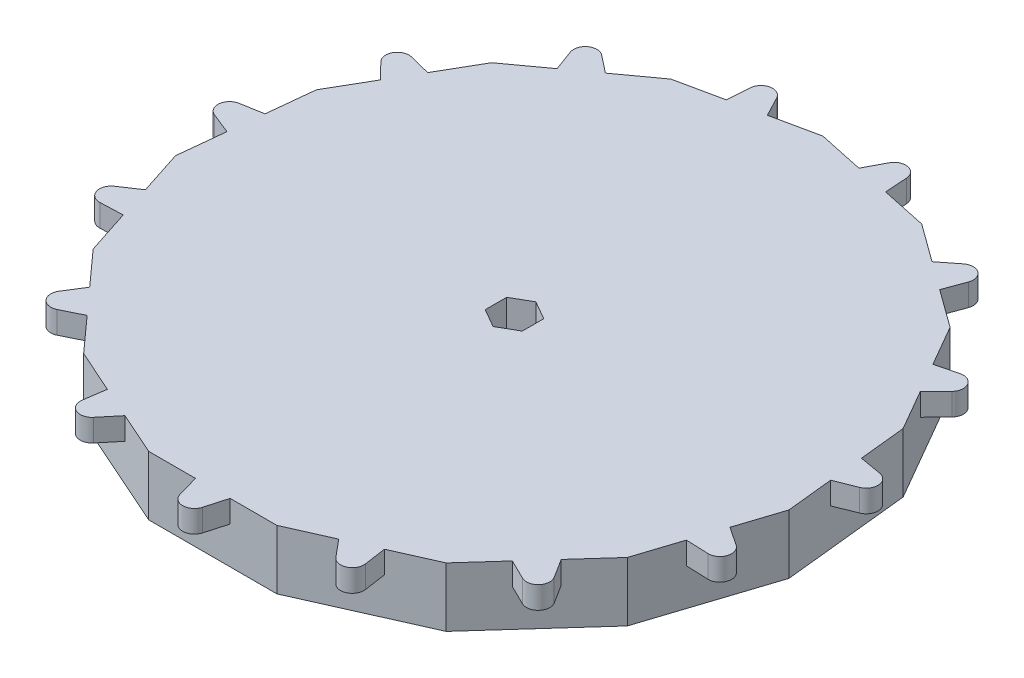
SolidWorks part; units mm, degrees
ref_plane "Front Plane" through (0, 0, 0) normal (0, 0, 1) x (1, 0, 0)
ref_plane "Top Plane" through (0, 0, 0) normal (0, 1, 0) x (1, 0, 0)
ref_plane "Right Plane" through (0, 0, 0) normal (1, 0, 0) x (0, 0, -1)
sketch "Sketch2" plane through (0, 0, 0) normal (0, 1, 0) x (1, 0, 0)
  line L18 (-48.0899, -66.1901) -> (-17.0104, -80.0275) construction
  line L37 (0, 81.8154) -> (-33.2773, 74.7421) construction
  line L38 (-33.2773, 74.7421) -> (-60.8007, 54.7452) construction
  line L39 (-60.8007, 54.7452) -> (-77.8111, 25.2824) construction
  line L40 (-77.8111, 25.2824) -> (-81.3672, -8.552) construction
  line L41 (-81.3672, -8.552) -> (-70.8542, -40.9077) construction
  line L42 (-70.8542, -40.9077) -> (-48.0899, -66.1901) construction
  line L43 (-17.0104, -80.0275) -> (17.0104, -80.0275) construction
  line L44 (17.0104, -80.0275) -> (48.0899, -66.1901) construction
  line L45 (48.0899, -66.1901) -> (70.8542, -40.9077) construction
  line L46 (70.8542, -40.9077) -> (81.3672, -8.552) construction
  line L47 (81.3672, -8.552) -> (77.8111, 25.2824) construction
  line L48 (77.8111, 25.2824) -> (60.8007, 54.7452) construction
  line L49 (60.8007, 54.7452) -> (33.2773, 74.7421) construction
  line L50 (33.2773, 74.7421) -> (0, 81.8154) construction
  line L51 (16.1106, 75.7943) -> (17.0907, 80.4055) construction
  line L52 (0, 79.2187) -> (-32.2211, 72.3699)
  line L53 (-32.2211, 72.3699) -> (-58.8709, 53.0076)
  line L54 (-58.8709, 53.0076) -> (-75.3414, 24.4799)
  line L55 (-75.3414, 24.4799) -> (-78.7847, -8.2806)
  line L56 (-78.7847, -8.2806) -> (-68.6054, -39.6093)
  line L57 (-68.6054, -39.6093) -> (-46.5636, -64.0892)
  line L58 (-46.5636, -64.0892) -> (-16.4705, -77.4875)
  line L59 (-16.4705, -77.4875) -> (16.4705, -77.4875)
  line L60 (16.4705, -77.4875) -> (46.5636, -64.0892)
  line L61 (46.5636, -64.0892) -> (68.6054, -39.6093)
  line L62 (68.6054, -39.6093) -> (78.7847, -8.2806)
  line L63 (78.7847, -8.2806) -> (75.3414, 24.4799)
  line L64 (75.3414, 24.4799) -> (58.8709, 53.0076)
  line L65 (58.8709, 53.0076) -> (32.2211, 72.3699)
  line L66 (32.2211, 72.3699) -> (0, 79.2187)
  line L67 (11.7627, 76.7184) -> (14.4414, 81.8016)
  line L68 (20.4584, 74.8701) -> (20.0788, 80.6033)
  line L69 (41.95, 65.3014) -> (46.4646, 68.8556)
  line L70 (49.1421, 60.076) -> (51.1272, 65.468)
  line L71 (64.8837, 42.5933) -> (70.4536, 44.0039)
  line L72 (69.3287, 34.8943) -> (73.3353, 39.0127)
  line L73 (76.5984, 12.5203) -> (82.2606, 11.5435)
  line L74 (77.5277, 3.679) -> (82.863, 5.8117)
  line L75 (75.0686, -19.7175) -> (79.8439, -22.9129)
  line L76 (72.3215, -28.1724) -> (78.063, -28.3942)
  line L77 (60.5588, -48.546) -> (63.6216, -53.4074)
  line L78 (54.6102, -55.1526) -> (59.7651, -57.6904)
  line L79 (35.5777, -68.9805) -> (36.3984, -74.6673)
  line L80 (27.4563, -72.5963) -> (31.1333, -77.0115)
  line L81 (4.445, -77.4875) -> (2.8817, -83.0166)
  line L82 (-4.445, -77.4875) -> (-2.8817, -83.0166)
  line L83 (-27.4563, -72.5963) -> (-31.1333, -77.0115)
  line L84 (-35.5777, -68.9805) -> (-36.3984, -74.6673)
  line L85 (-54.6102, -55.1526) -> (-59.7651, -57.6904)
  line L86 (-60.5588, -48.546) -> (-63.6216, -53.4074)
  line L87 (-72.3215, -28.1724) -> (-78.063, -28.3942)
  line L88 (-75.0686, -19.7175) -> (-79.8439, -22.9129)
  line L89 (-77.5277, 3.679) -> (-82.863, 5.8117)
  line L90 (-76.5984, 12.5203) -> (-82.2606, 11.5435)
  line L91 (-69.3287, 34.8943) -> (-73.3353, 39.0127)
  line L92 (-64.8837, 42.5933) -> (-70.4536, 44.0039)
  line L93 (-49.1421, 60.076) -> (-51.1272, 65.468)
  line L94 (-41.95, 65.3014) -> (-46.4646, 68.8556)
  line L95 (-20.4584, 74.8701) -> (-20.0788, 80.6033)
  line L96 (-11.7627, 76.7184) -> (-14.4414, 81.8016)
  circle A0 centre (0, 0) radius 80.0275 construction
  circle A1 centre (0, 0) radius 77.4875 construction
  arc A2 (14.4414, 81.8016) -> (20.0788, 80.6033) centre (17.0907, 80.4055) cw
  arc A3 (46.4646, 68.8556) -> (51.1272, 65.468) centre (48.317, 66.5026) cw
  arc A4 (70.4536, 44.0039) -> (73.3353, 39.0127) centre (71.1888, 41.1009) cw
  arc A5 (82.2606, 11.5435) -> (82.863, 5.8117) centre (81.7515, 8.5924) cw
  arc A6 (79.8439, -22.9129) -> (78.063, -28.3942) centre (78.1785, -25.4017) cw
  arc A7 (63.6216, -53.4074) -> (59.7651, -57.6904) centre (61.0878, -55.0037) cw
  arc A8 (36.3984, -74.6673) -> (31.1333, -77.0115) centre (33.4345, -75.0951) cw
  arc A9 (2.8817, -83.0166) -> (-2.8817, -83.0166) centre (0, -82.2018) cw
  arc A10 (-31.1333, -77.0115) -> (-36.3984, -74.6673) centre (-33.4345, -75.0951) cw
  arc A11 (-59.7651, -57.6904) -> (-63.6216, -53.4074) centre (-61.0878, -55.0037) cw
  arc A12 (-78.063, -28.3942) -> (-79.8439, -22.9129) centre (-78.1785, -25.4017) cw
  arc A13 (-82.863, 5.8117) -> (-82.2606, 11.5435) centre (-81.7515, 8.5924) cw
  arc A14 (-73.3353, 39.0127) -> (-70.4536, 44.0039) centre (-71.1888, 41.1009) cw
  arc A15 (-51.1272, 65.468) -> (-46.4646, 68.8556) centre (-48.317, 66.5026) cw
  arc A16 (-20.0788, 80.6033) -> (-14.4414, 81.8016) centre (-17.0907, 80.4055) cw
  point P36 (11.7627, 76.7184)
  point P37 (20.4584, 74.8701)
  point P114 (0, 0)
  dimension "D6" = 2.9947
  dimension "D1" = 2.54
  dimension "D2" = 34.0208
  dimension "D3" = 4.7142
  dimension "D4" = 4.445
  dimension "D5" = 4.445
  dimension "D7" = 15
extrude "Boss-Extrude1" add sketch "Sketch2" along normal blind 5.715 contours L65 L66 L52 L53 L54 L55 L56 L57 L58 L59 L60 L61 L62 L63 L64 | A10 L83 L58 L84 | A9 L81 L59 L82 | A8 L79 L60 L80 | A7 L77 L61 L78 | A6 L75 L62 L76 | A5 L73 L63 L74 | A4 L71 L64 L72 | A3 L69 L65 L70 | A2 L67 L66 L68 | A16 L95 L52 L96 | A15 L93 L53 L94 | A14 L91 L54 L92 | A13 L89 L55 L90 | A12 L87 L56 L88 | A11 L85 L57 L86
sketch "Sketch4" plane through (0, 0, 0) normal (0, -1, 0) x (-1, 0, 0)
  line L1 (-9.525, 65.9911) -> (9.525, 65.9911)
  line L2 (-9.525, 65.9911) -> (-9.525, -65.9911)
  line L3 (-9.525, -65.9911) -> (9.525, -65.9911)
  line L4 (9.525, 65.9911) -> (9.525, -65.9911)
  line L5 (-9.525, 65.9911) -> (9.525, -65.9911) construction
  line L6 (-9.525, -65.9911) -> (9.525, 65.9911) construction
  line L7 (65.9911, 9.525) -> (-65.9911, 9.525)
  line L8 (65.9911, 9.525) -> (65.9911, -9.525)
  line L9 (65.9911, -9.525) -> (-65.9911, -9.525)
  line L10 (-65.9911, 9.525) -> (-65.9911, -9.525)
  line L11 (65.9911, 9.525) -> (-65.9911, -9.525) construction
  line L12 (65.9911, -9.525) -> (-65.9911, 9.525) construction
  circle A0 centre (0, 0) radius 73.025
  circle A1 centre (0, 0) radius 66.675
  dimension "D1" = 146.05
  dimension "D2" = 133.35
  dimension "D3" = 19.05
  dimension "D4" = 19.05
extrude "Boss-Extrude2" add sketch "Sketch4" along normal blind 6.35 contours A0 A1 | L4 L9 L2 L3 | L9 L8 L7 L4 | L7 L10 L9 L2 | L9 L4 L7 L2 | L7 L4 L1 L2 | L3 A1 | L8 A1 | L10 A1 | L1 A1
sketch "Sketch5" plane through (0, -6.35, 0) normal (0, -1, 0) x (-1, 0, 0)
  circle A0 centre (0, 0) radius 66.675
  circle A1 centre (0, 0) radius 73.025
extrude "Boss-Extrude3" add sketch "Sketch5" along normal blind 6.35
sketch "Sketch6" plane through (0, 0, 0) normal (0, 0, 1) x (1, 0, 0)
  line L0 (0, -12.7) -> (-14.5955, -12.7)
  line L1 (0, -12.7) -> (0, 0)
  line L2 (0, 0) -> (-66.675, 0)
  spline S0 degree 3 poles (-14.5955, -12.7) (-31.688, -7.3967) (-49.2905, -4.1267) (-66.675, 0) knots 0 0 0 0 1 1 1 1
  dimension "D1" = 66.675
  dimension "D2" = 12.7
revolve "Revolve1" add sketch "Sketch6" angle 360 about L1
sketch "Sketch3" plane through (0, 5.715, 0) normal (0, 1, 0) x (1, 0, 0)
  line L1 (0, 5.4993) -> (-4.7625, 2.7496)
  line L2 (-4.7625, 2.7496) -> (-4.7625, -2.7496)
  line L3 (-4.7625, -2.7496) -> (0, -5.4993)
  line L4 (0, -5.4993) -> (4.7625, -2.7496)
  line L5 (4.7625, -2.7496) -> (4.7625, 2.7496)
  line L6 (4.7625, 2.7496) -> (0, 5.4993)
  circle A0 centre (0, 0) radius 4.7625 construction
  dimension "D1" = 9.525
extrude "Cut-Extrude1" cut sketch "Sketch3" against normal through all
sketch "Sketch7" plane through (0, 0, 0) normal (0, -1, 0) x (-1, 0, 0)
  line L1 (0, 79.2187) -> (-32.2211, 72.3699)
  line L2 (-32.2211, 72.3699) -> (-58.8709, 53.0076)
  line L3 (-58.8709, 53.0076) -> (-75.3414, 24.4799)
  line L4 (-75.3414, 24.4799) -> (-78.7847, -8.2806)
  line L5 (-78.7847, -8.2806) -> (-68.6054, -39.6093)
  line L6 (-68.6054, -39.6093) -> (-46.5636, -64.0892)
  line L7 (-46.5636, -64.0892) -> (-16.4705, -77.4875)
  line L8 (-16.4705, -77.4875) -> (16.4705, -77.4875)
  line L9 (16.4705, -77.4875) -> (46.5636, -64.0892)
  line L10 (46.5636, -64.0892) -> (68.6054, -39.6093)
  line L11 (68.6054, -39.6093) -> (78.7847, -8.2806)
  line L12 (78.7847, -8.2806) -> (75.3414, 24.4799)
  line L13 (75.3414, 24.4799) -> (58.8709, 53.0076)
  line L14 (58.8709, 53.0076) -> (32.2211, 72.3699)
  line L15 (32.2211, 72.3699) -> (0, 79.2187)
  circle A0 centre (0, 0) radius 73.025
  circle A1 centre (0, 0) radius 77.4875 construction
extrude "Boss-Extrude5" add sketch "Sketch7" along normal blind 9.525
